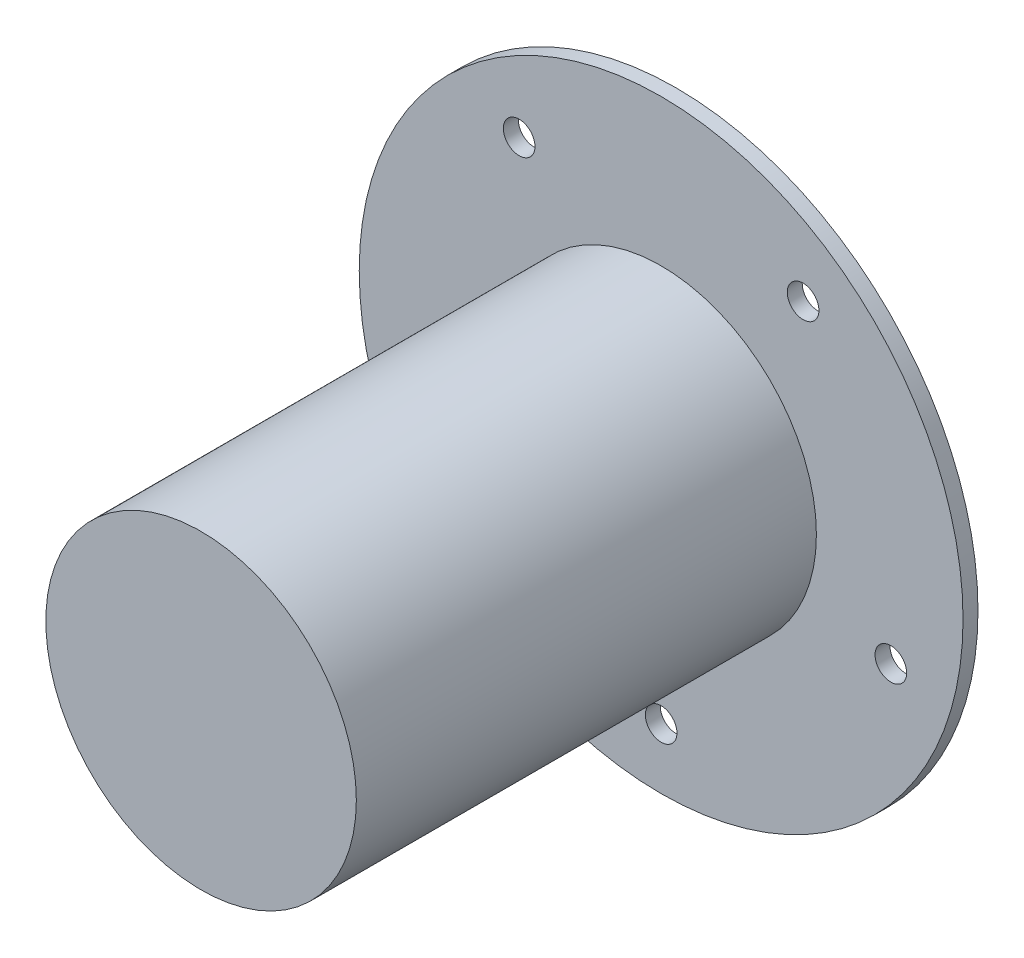
SolidWorks part; units mm, degrees
ref_plane "Front Plane" through (0, 0, 0) normal (0, 0, 1) x (1, 0, 0)
ref_plane "Top Plane" through (0, 0, 0) normal (0, 1, 0) x (1, 0, 0)
ref_plane "Right Plane" through (0, 0, 0) normal (1, 0, 0) x (0, 0, -1)
sketch "Sketch1" plane through (0, 0, 0) normal (0, 0, 1) x (1, 0, 0)
  circle A0 centre (0, 0) radius 52.5
  dimension "D1" = 105
extrude "Boss-Extrude1" add sketch "Sketch1" against normal blind 2.6
sketch "Sketch2" plane through (0, 0, 0) normal (0, 0, 1) x (1, 0, 0)
  circle A0 centre (0, 0) radius 27
  dimension "D1" = 54
extrude "Boss-Extrude2" add sketch "Sketch2" along normal blind 80
sketch "Sketch3" plane through (0, 0, 0) normal (0, 0, 1) x (1, 0, 0)
  circle A0 centre (-39.9444, -12.9787) radius 2.75
  circle A1 centre (0, 0) radius 27 construction
  dimension "D1" = 5.5
  dimension "D2" = 39.9444
  dimension "D3" = 12.9787
extrude "Cut-Extrude1" cut sketch "Sketch3" against normal through all
pattern_circular "CirPattern1" count 5 over 360 about axis through (0, 0, 0) along (0, 0, 1) of "Cut-Extrude1"
